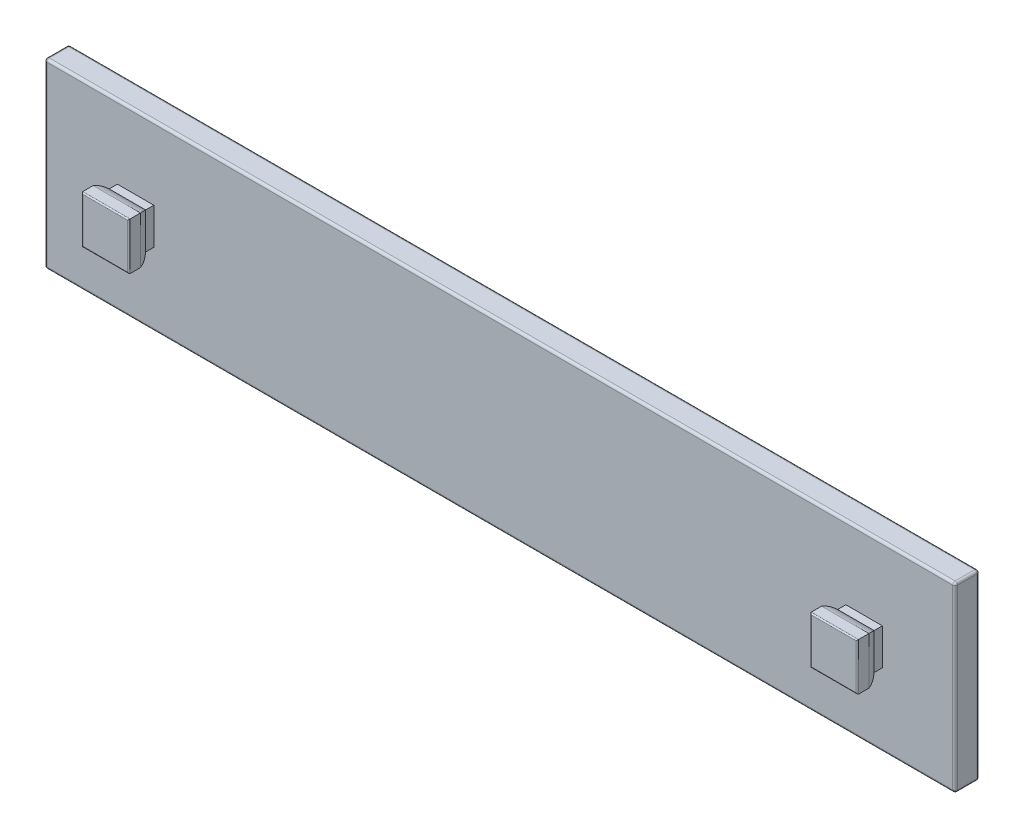
SolidWorks part; units mm, degrees
ref_plane "前视基准面" through (0, 0, 0) normal (0, 0, 1) x (1, 0, 0)
ref_plane "上视基准面" through (0, 0, 0) normal (0, 1, 0) x (1, 0, 0)
ref_plane "右视基准面" through (0, 0, 0) normal (1, 0, 0) x (0, 0, -1)
sketch "草图1" plane through (0, 0, 0) normal (0, 0, 1) x (1, 0, 0)
  line L1 (-37.5, -7.5) -> (37.5, -7.5)
  line L2 (-37.5, -7.5) -> (-37.5, 7.5)
  line L3 (-37.5, 7.5) -> (37.5, 7.5)
  line L4 (37.5, -7.5) -> (37.5, 7.5)
extrude "凸台-拉伸1" add sketch "草图1" against normal blind 2
sketch "草图2" plane through (0, 0, 0) normal (0, 0, 1) x (1, 0, 0)
  line L1 (-31.5, -1.5) -> (-28.5, -1.5)
  line L2 (-31.5, -1.5) -> (-31.5, 1.5)
  line L3 (-31.5, 1.5) -> (-28.5, 1.5)
  line L4 (-28.5, -1.5) -> (-28.5, 1.5)
  line L5 (28.5, 1.5) -> (31.5, 1.5)
  line L6 (28.5, 1.5) -> (28.5, -1.5)
  line L7 (28.5, -1.5) -> (31.5, -1.5)
  line L8 (31.5, 1.5) -> (31.5, -1.5)
extrude "凸台-拉伸2" add sketch "草图2" along normal blind 1
sketch "草图3" plane through (0, 0, 0) normal (0, -1, 0) x (1, 0, 0)
  line L0 (-31.95, 2.5) -> (-28.05, 2.5)
  line L1 (-31.95, 2.5) -> (-31.95, 1.5556)
  line L2 (-28.05, 2.5) -> (-28.05, 1.5556)
  line L3 (0, 4.2333) -> (0, -3.656) construction
  line L4 (-31.5, 1) -> (-31.5, 0) construction
  line L5 (-31.5, 0.6771) -> (-28.5, 0.6771)
  line L6 (31.5, 0.6771) -> (28.5, 0.6771)
  line L7 (28.05, 2.5) -> (28.05, 1.5556)
  line L8 (31.95, 2.5) -> (31.95, 1.5556)
  line L9 (31.95, 2.5) -> (28.05, 2.5)
  arc A0 (28.5, 0.6771) -> (28.05, 1.5556) centre (30, 2) cw
  arc A1 (-31.95, 1.5556) -> (-31.5, 0.6771) centre (-30, 2) ccw
  arc A2 (-28.5, 0.6771) -> (-28.05, 1.5556) centre (-30, 2) ccw
  arc A3 (31.95, 1.5556) -> (31.5, 0.6771) centre (30, 2) cw
extrude "凸台-拉伸3" add sketch "草图3" along normal blind 2 and the other way blind 2
sketch "草图4" plane through (-31.95, 0, 0) normal (-1, 0, 0) x (0, 0, 1)
  line L0 (2.5, 1.95) -> (1.5556, 1.95)
  line L1 (0.6771, -2) -> (2.5, -2)
  line L2 (0.6771, -2) -> (0.6771, -1.5)
  line L3 (0.6771, 2) -> (2.5, 2)
  line L4 (2.5, -2) -> (2.5, -1.95)
  line L6 (2.5, -1.95) -> (1.5556, -1.95)
  line L7 (0.6771, 1.5) -> (0.6771, 2)
  line L8 (2.5, 1.95) -> (2.5, 2)
  arc A1 (0.6771, -1.5) -> (1.5556, -1.95) centre (2, 0) ccw
  arc A2 (1.5556, 1.95) -> (0.6771, 1.5) centre (2, 0) ccw
extrude "切除-拉伸1" cut sketch "草图4" against normal through all
fillet "圆角1" radius 0.1 8 edges at (28.05, 0, 2.5) (30, 1.95, 2.5) (31.95, 0, 2.5) (30, -1.95, 2.5) (-31.95, 0, 2.5) (-30, 1.95, 2.5) (-28.05, 0, 2.5) (-30, -1.95, 2.5)
fillet "圆角2" radius 0.2 12 edges at (0, -7.5, -2) (0, -7.5, 0) (-37.5, -7.5, -1) (-37.5, 0, -2) (-37.5, 0, 0) (37.5, 0, -2) (37.5, -7.5, -1) (37.5, 0, 0) (-37.5, 7.5, -1) (0, 7.5, -2) (37.5, 7.5, -1) (0, 7.5, 0)
